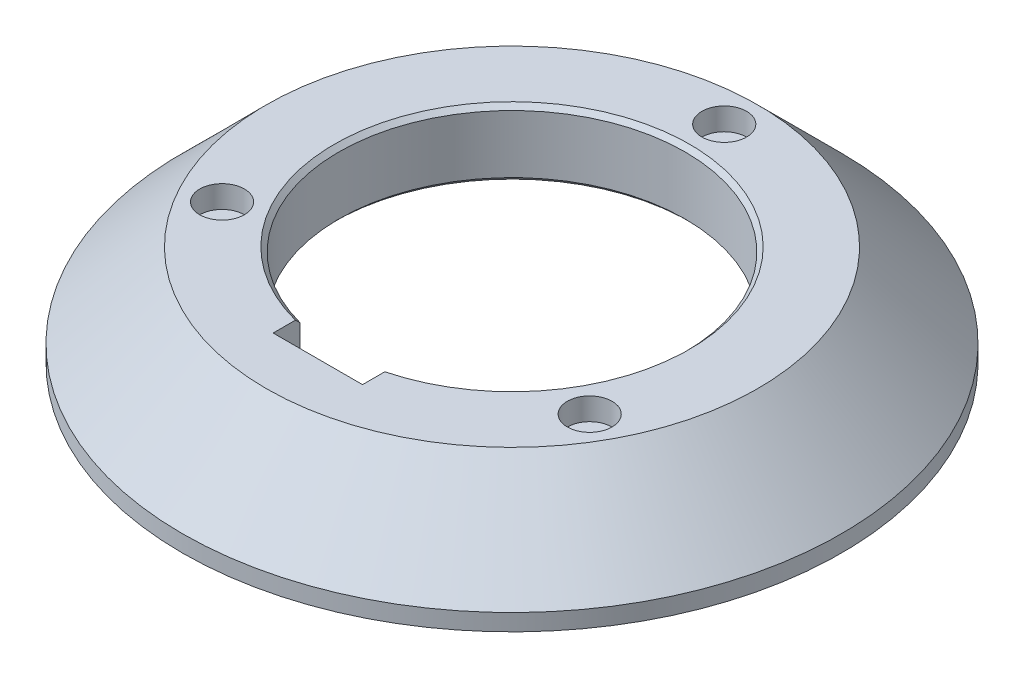
SolidWorks part; units mm, degrees
ref_plane "Спереди" through (0, 0, 0) normal (0, 0, 1) x (1, 0, 0)
ref_plane "Сверху" through (0, 0, 0) normal (0, 1, 0) x (1, 0, 0)
ref_plane "Справа" through (0, 0, 0) normal (1, 0, 0) x (0, 0, -1)
sketch "Эскиз1" plane through (0, 0, 0) normal (0, 0, 1) x (1, 0, 0)
  line L0 (0, 107.7506) -> (0, -115.6347) construction
  line L1 (77.5, 30) -> (77.5, 0)
  line L2 (77.5, 0) -> (117.5, 0)
  line L3 (117.5, 0) -> (132.5, -15)
  line L4 (132.5, -15) -> (147.5, -15)
  line L5 (147.5, -15) -> (147.5, -7.5)
  line L6 (147.5, -7.5) -> (110, 30)
  line L7 (110, 30) -> (77.5, 30)
  dimension "D1" = 295
  dimension "D2" = 220
  dimension "D3" = 45
  dimension "D4" = 235
  dimension "D5" = 155
  dimension "D6" = 45
  dimension "D7" = 15
revolve "Повернуть1" add sketch "Эскиз1" angle 360 about L0
chamfer "Фаска1" distance 2 angle 45 2 edges at (0, 0, 77.5) (0, 30, 77.5)
sketch "Эскиз2" plane through (0, 30, 0) normal (0, 1, 0) x (1, 0, 0)
  line L0 (0, 183.2159) -> (0, -176.2625) construction
  circle A0 centre (0, 0) radius 95 construction
  circle A1 centre (0, 95) radius 10
  dimension "D1" = 190
  dimension "D2" = 20
extrude "Вырез-Вытянуть1" cut sketch "Эскиз2" against normal blind 10
pattern_circular "Круговой массив1" count 3 over 360 about axis through (0, 0, 0) along (0, 1, 0) of "Вырез-Вытянуть1"
sketch "Эскиз3" plane through (0, 30, 0) normal (0, 1, 0) x (1, 0, 0)
  line L0 (0, 55.0843) -> (0, -155.657) construction
  line L1 (-209.5472, 0) -> (211.9356, 0) construction
  line L2 (0, 77.5) -> (-170.7128, 77.5) construction
  line L3 (-20, -86.9) -> (20, -86.9)
  line L4 (20, -86.9) -> (20, -62.046)
  line L5 (20, -62.046) -> (-20, -62.046)
  line L6 (-20, -62.046) -> (-20, -86.9)
  circle A0 centre (0, 0) radius 77.5 construction
  dimension "D1" = 164.4
  dimension "D2" = 40
extrude "Вырез-Вытянуть2" cut sketch "Эскиз3" against normal through all both and the other way through all
